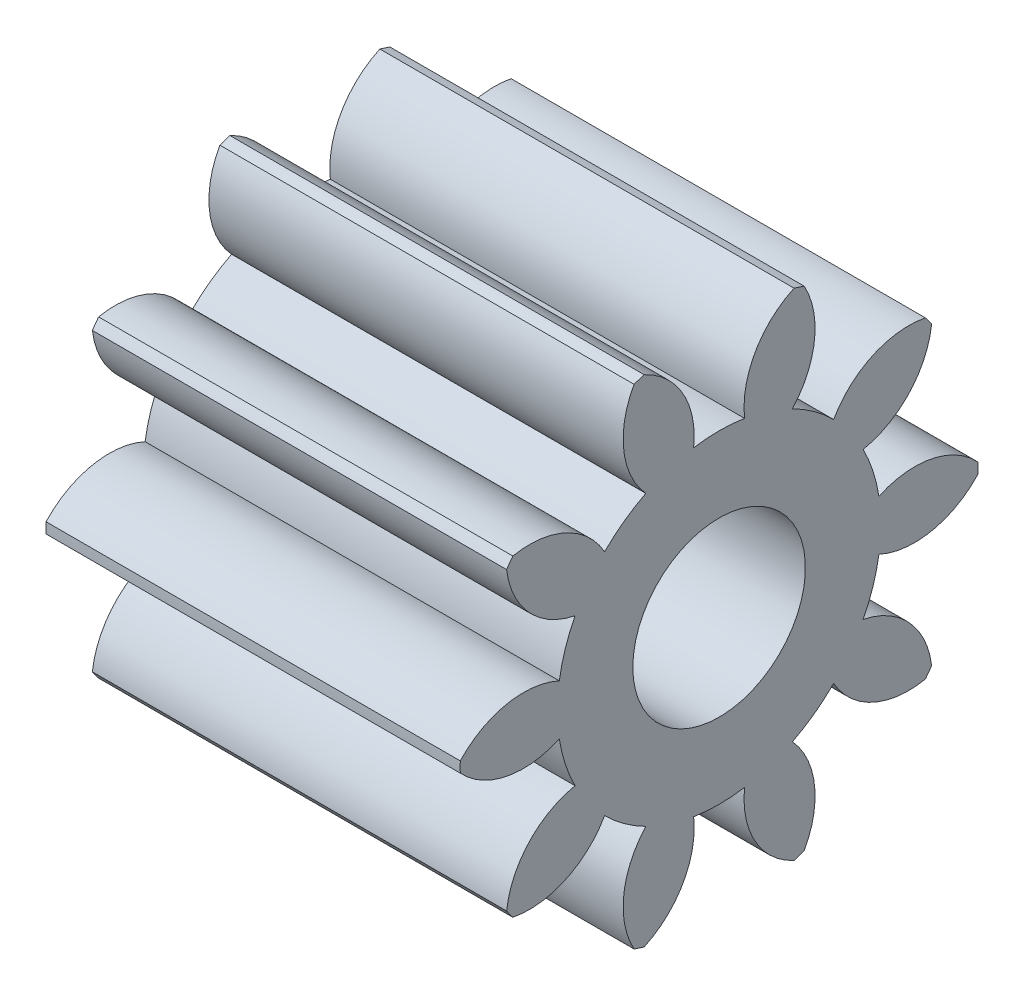
SolidWorks part; units mm, degrees
ref_plane "Plane1" through (0, 0, 0) normal (0, 0, 1) x (1, 0, 0)
ref_plane "Plane2" through (0, 0, 0) normal (0, 1, 0) x (1, 0, 0)
ref_plane "Plane3" through (0, 0, 0) normal (1, 0, 0) x (0, 0, -1)
sketch "HoldingSke" plane through (0, 0, 0) normal (0, 1, 0) x (1, 0, 0)
  line L0 (0, 0) -> (0.7878, -0.1389)
  line L1 (-15, 0) -> (100, 0) construction
  line L2 (0, 0) -> (-2.1039, 2.3779)
  line L3 (0, 0) -> (-11.863, 4.5341)
  line L4 (0, 0) -> (8.5048, 1.4996)
  line L5 (0, 0) -> (-46.8476, -17.4728)
  line L6 (0, 0) -> (-9.9476, -6.7116)
  line L7 (-2.1039, 2.3779) -> (8.6586, 51.2059)
  line L8 (-76.2, 54.61) -> (-75.3, 54.61)
  line L9 (-71.009, 38.7566) -> (-53.1078, 45.2721)
  line L10 (-76.2, 71.12) -> (104.1128, 71.12)
  line L11 (0, 0) -> (-12, 0)
  line L12 (-76.2, 101.6) -> (-76.155, 101.6)
  line L13 (24.9733, 27.94) -> (52.9518, 28.4284)
  line L14 (24.9733, 27.94) -> (24.9743, 27.94)
  line L15 (24.9733, 27.94) -> (100.4006, 29.5858)
  line L16 (-63.627, -1.25) -> (-12.827, -1.25)
  circle A0 centre (0, 0) radius 2.5
  circle A1 centre (0, 0) radius 4.6865
  circle A2 centre (0, 0) radius 37.5
  circle A3 centre (0, 0) radius 2.5
  dimension "MHD" = 9.373
  dimension "Hub_dia" = 75
  dimension "Bore" = 5
  dimension "MBD" = 5
  dimension "Num_teeth" = 10
  dimension "Pitch_radius" = 180.3128
  dimension "Pitch" = 0.8
  dimension "Width" = 12
  dimension "Overall_len" = 50
  dimension "Show_teeth" = 10
  dimension "Thickness" = 12
  dimension "OAL" = 50.0001
  dimension "T_dim" = 0.9
  dimension "Ap" = 20
  dimension "H" = 19.05
  dimension "Backlash" = 0.045
  dimension "Addendum_fac" = 1
  dimension "Dedendum_fac" = 1.25
  dimension "Clearance_fac" = 0.25
  dimension "Dedendum_add" = 0.001
  dimension "Module" = 1.25
sketch "BasProSke" plane through (0, 0, 0) normal (0, 1, 0) x (1, 0, 0)
  line L0 (-10, 0) -> (60, 0) construction
  line L1 (0, 0) -> (0, 7.5)
  line L2 (0, 0) -> (12, 0)
  line L3 (12, 0) -> (12, 7.5)
  line L4 (12, 7.5) -> (0, 7.5)
  dimension "Diameter" = 15
  dimension "Thickness" = 12
revolve "Base-Revolve" add sketch "BasProSke" angle 360 about L0
sketch "TooCutSke" plane through (0, 0, 0) normal (1, 0, 0) x (0, 0, -1)
  line L1 (0, 0) -> (0, 107) construction
  line L2 (0, 0) -> (-1.0563, 6.1601) construction
  line L3 (0, 0) -> (-3.8225, 11.7646) construction
  line L4 (-1.0563, 6.1601) -> (-1.9113, 5.8823) construction
  arc A0 (0.7377, 4.6281) -> (-0.7377, 4.6281) centre (0, 0) ccw
  arc A1 (2.2058, 7.1949) -> (-2.2058, 7.1949) centre (0, 0) ccw
  circle A2 centre (0, 0) radius 6.25 construction
  circle A3 centre (0, 0) radius 5.8731 construction
  arc A4 (-0.7377, 4.6281) -> (-2.2058, 7.1949) centre (-3.2217, 4.9106) ccw
  arc A5 (2.2058, 7.1949) -> (0.7377, 4.6281) centre (3.2217, 4.9106) ccw
  dimension "Root_dia" = 9.373
  dimension "Overcut_dia" = 15.0508
  dimension "Pitch_dia" = 12.5
  dimension "Base_dia" = 11.7462
  dimension "Flank_rad" = 2.5
  dimension "Half_ang" = 18
  dimension "Half_CT" = 0.899
extrude "ToothCut" cut sketch "TooCutSke" along normal through all
fillet "Breaks" [suppressed] radius 0.025
fillet "RootFillets" [suppressed] radius 0.3135
pattern_circular "TeethCuts" count 10 over 360 about axis through (0, 0, 0) along (1, 0, 0) of "ToothCut", "RootFillets", "Breaks"
sketch "HubNeaOneSke" plane through (0, 0, 0) normal (-1, 0, 0) x (0, 0, 1)
  circle A0 centre (0, 0) radius 4.6865
  dimension "Diameter" = 9.373
extrude "HubNearOne" [suppressed] add sketch "HubNeaOneSke" along normal blind 38.0001
sketch "HubNeaBotSke" plane through (0, 0, 0) normal (-1, 0, 0) x (0, 0, 1)
  circle A0 centre (0, 0) radius 4.6865
  dimension "Diameter" = 9.373
extrude "HubNearBoth" [suppressed] add sketch "HubNeaBotSke" along normal blind 19
ref_plane "FarPln" through (12, 0, 0) normal (1, 0, 0) x (0, 0, -1)
sketch "HubFarSke" plane through (12, 0, 0) normal (1, 0, 0) x (0, 0, -1)
  circle A0 centre (0, 0) radius 4.6865
  dimension "Diameter" = 9.373
extrude "HubFar" [suppressed] add sketch "HubFarSke" along normal blind 19
sketch "BorSke" plane through (0, 0, 0) normal (1, 0, 0) x (0, 0, -1)
  circle A0 centre (0, 0) radius 2.5
  dimension "Diameter" = 5
extrude "Bore" cut sketch "BorSke" along normal mid plane 100.0001
sketch "KeySke" plane through (0, 0, 0) normal (1, 0, 0) x (0, 0, -1)
  line L0 (-1, 0) -> (-1, 3.4)
  line L1 (-1, 3.4) -> (1, 3.4)
  line L2 (1, 3.4) -> (1, 0)
  line L3 (0, 0) -> (0, 34) construction
  line L4 (-1, 0) -> (1, 0)
  dimension "Offset" = 3.4
  dimension "Width" = 2
extrude "Keyway" [suppressed] cut sketch "KeySke" along normal mid plane 100.0001
pattern_circular "Keyway2" [suppressed] count 2 every 90 about axis through (-10, 0, 0) along (1, 0, 0)
sketch "Эскиз1" plane through (12, 0, 0) normal (1, 0, 0) x (0, 0, -1)
  circle A0 centre (0, 0) radius 7.5
equation "' \"Module@HoldingSke\" = 6.35"
equation "' \"Num_teeth@HoldingSke\" = 12"
equation "' \"Ap@HoldingSke\" =  20"
equation "' \"Width@HoldingSke\" = 0.5 * 25.4"
equation "' \"Hub_dia@HoldingSke\"= 1 * 25.4"
equation "' \"Overall_len@HoldingSke\" = 1.0 * 25.4"
equation "' \"Bore@HoldingSke\" = 0.75 * 25.4"
equation "' \"T_dim@HoldingSke\" = 0.1 * 25.4"
equation "' \"Width@KeySke\" = 0.25 * 25.4"
equation "' \"Show_teeth@HoldingSke\" = 13"
equation "' \"Backlash@HoldingSke\" = 0.009 * 25.4"
equation "' \"Addendum_fac@HoldingSke\" = 1.0"
equation "' \"Dedendum_fac@HoldingSke\" = 1.25"
equation "' \"Dedendum_add@HoldingSke\" = 0.00005 * 25.4"
equation "' \"Clearance_fac@HoldingSke\" = 0.25"
equation "\"Pitch@HoldingSke\" = 1 / \"Module@HoldingSke\""
equation "\"Overcut_dia@TooCutSke\" = (\"Num_teeth@HoldingSke\" + 2 * \"Addendum_fac@HoldingSke\") / \"Pitch@HoldingSke\" + 0.002 * 25.4"
equation "\"Pitch_dia@TooCutSke\" = \"Num_teeth@HoldingSke\" / \"Pitch@HoldingSke\""
equation "\"Base_dia@TooCutSke\" = \"Num_teeth@HoldingSke\" / \"Pitch@HoldingSke\" * cos((\"Ap@HoldingSke\"  * 3.14159265 / 180))"
equation "\"Root_dia@TooCutSke\" = (\"Num_teeth@HoldingSke\" + 2) / \"Pitch@HoldingSke\" - 2 * (\"Addendum_fac@HoldingSke\" + \"Dedendum_fac@HoldingSke\") / \"Pitch@HoldingSke\" - \"Dedendum_add@HoldingSke\" * 2"
equation "\"Half_ang@TooCutSke\" = 180 / \"Num_teeth@HoldingSke\""
equation "\"Half_CT@TooCutSke\" = \"Num_teeth@HoldingSke\" / \"Pitch@HoldingSke\" * sin((3.14159265 / 2 / \"Num_teeth@HoldingSke\")) / 2 - 7 * \"Backlash@HoldingSke\" / 4"
equation "\"Flank_rad@TooCutSke\" = \"Num_teeth@HoldingSke\" / \"Pitch@HoldingSke\" / 5"
equation "\"Radius@RootFillets\" = \"Clearance_fac@HoldingSke\" / \"Pitch@HoldingSke\" + \"Dedendum_add@HoldingSke\""
equation "\"Break_rad@Breaks\" = 0.02 / \"Pitch@HoldingSke\""
equation "\"Thickness@HoldingSke\" = \"Width@HoldingSke\""
equation "\"OAL@HoldingSke\" = \"Thickness@HoldingSke\""
equation "\"MHD@HoldingSke\" = (\"Num_teeth@HoldingSke\" + 2) / \"Pitch@HoldingSke\" - 2 * (\"Addendum_fac@HoldingSke\" + \"Dedendum_fac@HoldingSke\")  / \"Pitch@HoldingSke\" - \"Dedendum_add@HoldingSke\" * 2"
equation "\"MBD@HoldingSke\" = (\"Num_teeth@HoldingSke\" + 2) / \"Pitch@HoldingSke\" - 2 * (\"Addendum_fac@HoldingSke\" + \"Dedendum_fac@HoldingSke\")  / \"Pitch@HoldingSke\" - \"Dedendum_add@HoldingSke\" * 2 - 0.002 * 25.4"
equation "\"MHD@HoldingSke\" = ((sgn( \"MHD@HoldingSke\" - \"Hub_dia@HoldingSke\" )-1)*( \"MHD@HoldingSke\" - \"Hub_dia@HoldingSke\" ))/-2+ \"Hub_dia@HoldingSke\""
equation "\"MBD@HoldingSke\" = ((sgn( \"MBD@HoldingSke\" - \"Bore@HoldingSke\" )-1)*( \"MBD@HoldingSke\" - \"Bore@HoldingSke\" ))/-2+ \"Bore@HoldingSke\""
equation "\"OAL@HoldingSke\" = ((sgn( \"OAL@HoldingSke\" - \"Overall_len@HoldingSke\" )+1)*( \"OAL@HoldingSke\" - \"Overall_len@HoldingSke\" ))/2 + \"Overall_len@HoldingSke\" + 0.000002 * 25.4"
equation "\"Num_teeth@TeethCuts\" = int( \"Show_teeth@HoldingSke\" ) + 1"
equation "\"Num_teeth@TeethCuts\" = ((sgn( \"Num_teeth@TeethCuts\" - \"Num_teeth@HoldingSke\" )-1)*( \"Num_teeth@TeethCuts\" - \"Num_teeth@HoldingSke\" ))/-2+ \"Num_teeth@HoldingSke\""
equation "\"Num_teeth@TeethCuts\" = ((sgn( \"Num_teeth@TeethCuts\" - 2.0)+1)*( \"Num_teeth@TeethCuts\" - 2.0))/2 +2.0"
equation "\"Angle@TeethCuts\" = 360.0 / \"Num_teeth@HoldingSke\""
equation "\"Diameter@BasProSke\" = (\"Num_teeth@HoldingSke\" + 2 * \"Addendum_fac@HoldingSke\") / \"Pitch@HoldingSke\""
equation "\"Thickness@BasProSke\"  = \"Thickness@HoldingSke\""
equation "' \"Fillet_rad@BasProSke\" =  \"Thickness@HoldingSke\" * 0.05"
equation "\"MHD@HoldingSke\" = ((sgn( \"MHD@HoldingSke\" - \"Root_dia@TooCutSke\" )-1)*( \"MHD@HoldingSke\" - \"Root_dia@TooCutSke\" ))/-2+ \"Root_dia@TooCutSke\""
equation "\"Diameter@HubNeaOneSke\" = \"MHD@HoldingSke\""
equation "\"Length@HubNearOne\" = \"OAL@HoldingSke\" - \"Thickness@BasProSke\""
equation "\"Diameter@HubNeaBotSke\" = \"MHD@HoldingSke\""
equation "\"Length@HubNearBoth\" = ( \"OAL@HoldingSke\" - \"Thickness@BasProSke\" ) / 2.0"
equation "\"Thickness@FarPln\" = \"Thickness@BasProSke\""
equation "\"Diameter@HubFarSke\" = \"MHD@HoldingSke\""
equation "\"Length@HubFar\" = ( \"OAL@HoldingSke\" - \"Thickness@BasProSke\" ) / 2.0"
equation "\"Diameter@BorSke\" = \"MBD@HoldingSke\""
equation "\"D1@Bore\" = \"OAL@HoldingSke\" * 2.0"
equation "\"D1@Keyway\" = \"OAL@HoldingSke\" * 2.0"
equation "\"Offset@KeySke\" = \"T_dim@HoldingSke\" + \"MBD@HoldingSke\" / 2.0"
